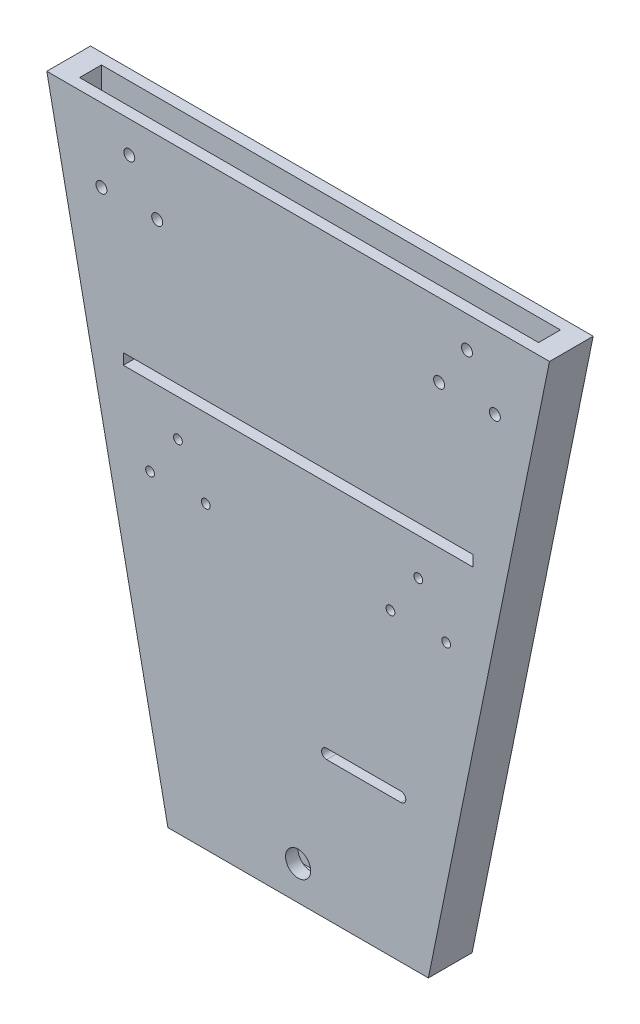
SolidWorks part; units mm, degrees
ref_plane "前视基准面" through (0, 0, 0) normal (0, 0, 1) x (1, 0, 0)
ref_plane "上视基准面" through (0, 0, 0) normal (0, 1, 0) x (1, 0, 0)
ref_plane "右视基准面" through (0, 0, 0) normal (1, 0, 0) x (0, 0, -1)
other "Configuration Table"
sketch "草图1" plane through (0, 0, 0) normal (0, 0, 1) x (1, 0, 0)
  line L0 (0, 0) -> (0, 50.6623) construction
  line L1 (-115, 220) -> (115, 220)
  line L2 (-60, -50) -> (60, -50) construction
  line L3 (-115, 220) -> (-60, -50)
  line L4 (115, 220) -> (60, -50)
  line L5 (-60, -50) -> (-59.5926, -52)
  line L6 (-59.5926, -52) -> (59.5926, -52)
  line L7 (59.5926, -52) -> (60, -50)
  point P6 (0, 220)
  point P7 (0, -50)
  dimension "D1" = 230
  dimension "D2" = 120
  dimension "D3" = 270
  dimension "D4" = 50
  dimension "D5" = 2
extrude "凸台-拉伸1" add sketch "草图1" along normal blind 20
sketch "草图3" plane through (0, 220, 0) normal (0, 1, 0) x (1, 0, 0)
  line L0 (115, -20) -> (-115, -20) construction
  line L1 (-105, -5) -> (105, -5)
  line L2 (-105, -5) -> (-105, -15)
  line L3 (-105, -15) -> (105, -15)
  line L4 (105, -5) -> (105, -15)
  line L5 (-105, -5) -> (105, -15) construction
  line L6 (-105, -15) -> (105, -5) construction
  line L8 (-115, -20) -> (-115, 0) construction
  point P4 (0, -10)
  dimension "D1" = 210
  dimension "D2" = 10
  dimension "D3" = 10
  dimension "D4" = 115
extrude "切除-拉伸1" cut sketch "草图3" against normal blind 15
sketch "草图4" plane through (0, 0, 20) normal (0, 0, 1) x (1, 0, 0)
  line L0 (-96.3631, 128.51) -> (96.3631, 128.51)
  line L1 (-115, 220) -> (-59.5926, -52) construction
  line L2 (59.5926, -52) -> (115, 220) construction
  line L3 (-94.3261, 118.51) -> (94.3261, 118.51)
  line L4 (115, 220) -> (-115, 220) construction
  line L5 (0, 220) -> (0, -87.5938) construction
  line L6 (-80, 126.01) -> (80, 126.01)
  line L7 (-80, 126.01) -> (-80, 121.01)
  line L8 (-80, 121.01) -> (80, 121.01)
  line L9 (80, 126.01) -> (80, 121.01)
  line L10 (-80, 126.01) -> (80, 121.01) construction
  line L11 (-80, 121.01) -> (80, 126.01) construction
  point P14 (0, 123.51)
  dimension "D1" = 10
  dimension "D2" = 91.49
  dimension "D3" = 160
  dimension "D4" = 5
  dimension "D5" = 5
extrude "切除-拉伸2" cut sketch "草图4" against normal blind 10 contours L9 L6 L7 L8
sketch "草图5" plane through (0, 0, 20) normal (0, 0, 1) x (1, 0, 0)
  line L0 (0, 220) -> (0, -61.0662) construction
  line L1 (-96.3631, 128.51) -> (96.3631, 128.51)
  line L2 (-115, 220) -> (-59.5926, -52) construction
  line L3 (59.5926, -52) -> (115, 220) construction
  line L4 (-94.3261, 118.51) -> (94.3261, 118.51)
  line L5 (115, 220) -> (-115, 220) construction
  circle A0 centre (-77.25, 205.6426) radius 2.5
  circle A1 centre (-90, 186.5) radius 2.5
  circle A2 centre (-64.5, 186.5) radius 2.5
  circle A3 centre (-55, 104.1526) radius 2
  circle A4 centre (-67.75, 85.01) radius 2
  circle A5 centre (-42.25, 85.01) radius 2
  circle A6 centre (42.25, 85.01) radius 2
  circle A7 centre (67.75, 85.01) radius 2
  circle A8 centre (55, 104.1526) radius 2
  circle A9 centre (64.5, 186.5) radius 2.5
  circle A10 centre (90, 186.5) radius 2.5
  circle A11 centre (77.25, 205.6426) radius 2.5
  dimension "D8" = 5
  dimension "D9" = 5
  dimension "D10" = 5
  dimension "D12" = 4
  dimension "D13" = 4
  dimension "D14" = 4
  dimension "D1" = 10
  dimension "D2" = 91.49
  dimension "D3" = 33.5
  dimension "D4" = 33.5
  dimension "D5" = 23
  dimension "D6" = 23
  dimension "D7" = 25.5
  dimension "D11" = 90
  dimension "D15" = 23
  dimension "D16" = 23
  dimension "D17" = 33.5
  dimension "D18" = 33.5
  dimension "D19" = 25.5
  dimension "D20" = 55
extrude "切除-拉伸3" cut sketch "草图5" against normal blind 10 contours A0 | A2 | A1 | A11 | A10 | A9 | A3 | A5 | A4 | A8 | A6 | A7
ref_plane "基准面1" through (0, 0, 10) normal (0, 0, -1) x (-1, 0, 0)
sketch "草图6" plane through (0, 0, 10) normal (0, 0, -1) x (-1, 0, 0)
  line L0 (0, 220) -> (0, -76.53) construction
  line L1 (0, -49.69) -> (17.4867, -49.69)
  line L2 (-115, 220) -> (115, 220) construction
  line L3 (17.4867, -49.69) -> (12.1089, -23.29)
  line L4 (0, -23.29) -> (12.1089, -23.29)
  line L6 (-59.5926, -52) -> (-115, 220) construction
  arc A0 (0, -23.29) -> (0, -49.69) centre (0, -36.49) ccw
  dimension "D2" = 26.4
  dimension "D1" = 256.49
  dimension "D3" = 14.5
extrude "切除-拉伸4" cut sketch "草图6" against normal mid plane 8.6
sketch "草图7" plane through (0, 0, 0) normal (0, 0, -1) x (-1, 0, 0)
  line L0 (0, 220) -> (0, -74.3263) construction
  line L2 (-115, 220) -> (115, 220) construction
  line L6 (-59.5926, -52) -> (59.5926, -52)
  line L7 (59.5926, -52) -> (115, 220)
  line L8 (-59.5926, -52) -> (59.5926, -52)
  line L9 (-115, 220) -> (-59.5926, -52)
  line L10 (115, 220) -> (-115, 220)
  line L11 (59.5926, -52) -> (115, 220)
  line L13 (-115, 220) -> (-59.5926, -52)
  line L14 (115, 220) -> (-115, 220)
  circle A0 centre (0, -36.49) radius 5.75
  dimension "D2" = 11.5
  dimension "D1" = 256.49
  dimension "D3" = 0
sketch "草图8" plane through (0, 0, 20) normal (0, 0, 1) x (1, 0, 0)
  line L4 (-115, 220) -> (-59.5926, -52)
  line L5 (-59.5926, -52) -> (59.5926, -52)
  line L6 (59.5926, -52) -> (115, 220)
  line L7 (115, 220) -> (-115, 220)
  line L8 (-115, 220) -> (-59.5926, -52)
  line L10 (59.5926, -52) -> (115, 220)
  line L11 (115, 220) -> (-115, 220)
  line L12 (-59.5926, -52) -> (59.5926, -52)
  circle A0 centre (0, -36.49) radius 5.75 construction
  circle A1 centre (0, -36.49) radius 5.75
  circle A2 centre (0, -36.49) radius 5.75
  dimension "D1" = 0
extrude "切除-拉伸6" cut sketch "草图8" against normal blind 15 contours A1
sketch "草图9" plane through (0, 0, 20) normal (0, 0, 1) x (1, 0, 0)
  line L0 (0, 200220) -> (0, -200074.3263) construction
  line L1 (0, 200220) -> (0, -200074.3263) construction
  line L2 (10, 13.51) -> (50, 13.51) construction
  line L3 (10, 17.51) -> (50, 17.51)
  line L4 (-115, 220) -> (-59.5926, -52)
  line L5 (-59.5926, -52) -> (59.5926, -52)
  line L6 (59.5926, -52) -> (115, 220)
  line L7 (115, 220) -> (-115, 220)
  line L8 (-115, 220) -> (-59.5926, -52)
  line L10 (59.5926, -52) -> (115, 220)
  line L11 (115, 220) -> (-115, 220)
  line L12 (10, 9.51) -> (50, 9.51)
  line L13 (-80, 126.01) -> (80, 126.01) construction
  line L14 (18.72, 154.01) -> (18.72, -36.49) construction
  line L15 (-18.72, 154.01) -> (-18.72, -36.49) construction
  line L16 (13, 13.51) -> (47, 13.51) construction
  line L17 (13, 15.76) -> (47, 15.76)
  line L18 (13, 11.26) -> (47, 11.26)
  line L23 (-59.5926, -52) -> (59.5926, -52)
  arc A0 (10, 17.51) -> (10, 9.51) centre (10, 13.51) ccw
  arc A1 (50, 9.51) -> (50, 17.51) centre (50, 13.51) ccw
  circle A2 centre (0, 154.01) radius 18.72 construction
  circle A3 centre (0, -36.49) radius 18.72 construction
  circle A4 centre (10, 13.51) radius 9.185 construction
  arc A5 (13, 15.76) -> (13, 11.26) centre (13, 13.51) ccw
  arc A6 (47, 11.26) -> (47, 15.76) centre (47, 13.51) ccw
  point P8 (30, 13.51)
  point P28 (30, 13.51)
  dimension "D6" = 37.44
  dimension "D7" = 37.44
  dimension "D9" = 18.37
  dimension "D2" = 40
  dimension "D3" = 50
  dimension "D4" = 10
  dimension "D5" = 8
  dimension "D8" = 28
  dimension "D10" = 37.44
  dimension "D11" = 4.5
  dimension "D12" = 3
  dimension "D13" = 3
  dimension "D1" = 0
extrude "切除-拉伸7" cut sketch "草图9" against normal through all contours L18 A6 L17 A5
sketch "草图10" plane through (0, 0, 0) normal (0, 0, -1) x (-1, 0, 0)
  line L2 (-10, 17.51) -> (-50, 17.51)
  line L3 (-50, 9.51) -> (-10, 9.51)
  line L4 (59.5926, -52) -> (115, 220)
  line L5 (-59.5926, -52) -> (59.5926, -52)
  line L6 (-115, 220) -> (-59.5926, -52)
  line L7 (115, 220) -> (-115, 220)
  line L8 (59.5926, -52) -> (115, 220)
  line L10 (-115, 220) -> (-59.5926, -52)
  line L11 (115, 220) -> (-115, 220)
  line L12 (-10, 17.51) -> (-50, 17.51)
  line L13 (-50, 9.51) -> (-10, 9.51)
  line L14 (-13, 15.76) -> (-47, 15.76)
  line L15 (-47, 11.26) -> (-13, 11.26)
  line L16 (-13, 15.76) -> (-47, 15.76)
  line L17 (-47, 11.26) -> (-13, 11.26)
  line L20 (-59.5926, -52) -> (59.5926, -52)
  arc A2 (-50, 17.51) -> (-50, 9.51) centre (-50, 13.51) ccw
  arc A3 (-10, 9.51) -> (-10, 17.51) centre (-10, 13.51) ccw
  arc A4 (-50, 17.51) -> (-50, 9.51) centre (-50, 13.51) ccw
  arc A5 (-10, 9.51) -> (-10, 17.51) centre (-10, 13.51) ccw
  arc A6 (-47, 15.76) -> (-47, 11.26) centre (-47, 13.51) ccw
  arc A7 (-13, 11.26) -> (-13, 15.76) centre (-13, 13.51) ccw
  arc A8 (-47, 15.76) -> (-47, 11.26) centre (-47, 13.51) ccw
  arc A9 (-13, 11.26) -> (-13, 15.76) centre (-13, 13.51) ccw
  arc M13 (-13, 15.76) -> (-13, 11.26) centre (-13, 13.51) cw
  line M14 (-13, 11.26) -> (-47, 11.26)
  arc M15 (-47, 11.26) -> (-47, 15.76) centre (-47, 13.51) cw
  line M16 (-47, 15.76) -> (-13, 15.76)
  dimension "D1" = 0
  dimension "D2" = 0
  dimension "D3" = 0
extrude "切除-拉伸8" cut sketch "草图10" against normal blind 8 contours L13 A5 L12 A4 M16 M13 M14 M15
sketch "草图14" [suppressed] plane through (0, 0, 20) normal (0, 0, 1) x (1, 0, 0)
  line L0 (10, 13.51) -> (50, 13.51) construction
  line L1 (10, 19.51) -> (50, 19.51)
  line L6 (13, 11.26) -> (47, 11.26)
  line L7 (47, 15.76) -> (13, 15.76)
  line L8 (-115, 220) -> (-60, -50)
  line L9 (115, 220) -> (-115, 220)
  line L10 (60, -50) -> (115, 220)
  line L11 (-60, -50) -> (60, -50)
  line L12 (-115, 220) -> (-60, -50)
  line L13 (115, 220) -> (-115, 220)
  line L14 (60, -50) -> (115, 220)
  line L15 (-60, -50) -> (60, -50)
  line L16 (13, 11.26) -> (47, 11.26)
  line L17 (47, 15.76) -> (13, 15.76)
  line L18 (10, 7.51) -> (50, 7.51)
  line L19 (0, 200220) -> (0, -200074.3263) construction
  arc A0 (10, 19.51) -> (10, 7.51) centre (10, 13.51) ccw
  arc A1 (50, 7.51) -> (50, 19.51) centre (50, 13.51) ccw
  arc A6 (47, 11.26) -> (47, 15.76) centre (47, 13.51) ccw
  arc A7 (13, 15.76) -> (13, 11.26) centre (13, 13.51) ccw
  arc A8 (47, 11.26) -> (47, 15.76) centre (47, 13.51) ccw
  arc A9 (13, 15.76) -> (13, 11.26) centre (13, 13.51) ccw
  point P12 (30, 13.51)
  dimension "D4" = 12
  dimension "D1" = 40
  dimension "D5" = 10
  dimension "D6" = 50
  dimension "D2" = 0
  dimension "D3" = 0
extrude "凸台-拉伸3" [suppressed] add sketch "草图14" along normal blind 17
